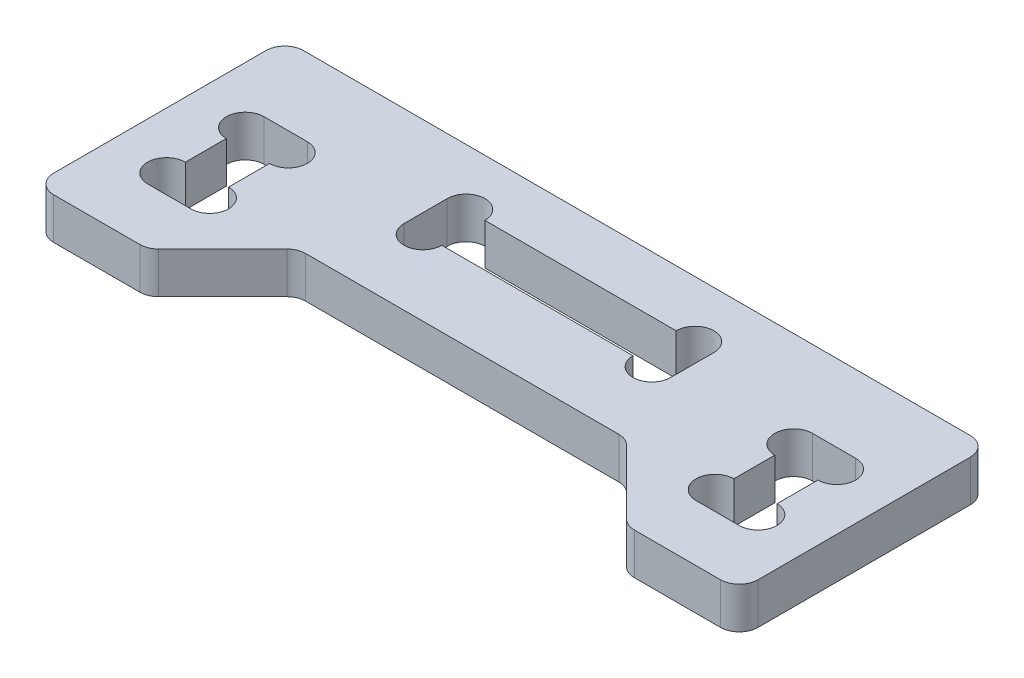
SolidWorks part; units mm, degrees
material "Thornel Mat VMA"
ref_plane "前视基准面" through (0, 0, 0) normal (0, 0, 1) x (1, 0, 0)
ref_plane "上视基准面" through (0, 0, 0) normal (0, 1, 0) x (1, 0, 0)
ref_plane "右视基准面" through (0, 0, 0) normal (1, 0, 0) x (0, 0, -1)
sketch "草图1" plane through (0, 0, 0) normal (0, 1, 0) x (1, 0, 0)
  line L0 (0, 0) -> (0, -4.8464) construction
  line L1 (7.1, -1.15) -> (-7.1, -1.15)
  line L2 (7.1, -1.15) -> (7.1, 1.15)
  line L3 (7.1, 1.15) -> (-7.1, 1.15)
  line L4 (-7.1, -1.15) -> (-7.1, 1.15)
  line L5 (7.1, -1.15) -> (-7.1, 1.15) construction
  line L6 (7.1, 1.15) -> (-7.1, -1.15) construction
  line L7 (-15.75, -6.15) -> (-13.45, -6.15)
  line L8 (-15.75, -6.15) -> (-15.75, 0.05)
  line L9 (-15.75, 0.05) -> (-13.45, 0.05)
  line L10 (-13.45, -6.15) -> (-13.45, 0.05)
  line L11 (-15.75, -6.15) -> (-13.45, 0.05) construction
  line L12 (-15.75, 0.05) -> (-13.45, -6.15) construction
  line L13 (15.75, 0.05) -> (13.45, 0.05)
  line L14 (13.45, -6.15) -> (13.45, 0.05)
  line L15 (15.75, -6.15) -> (13.45, -6.15)
  line L16 (15.75, -6.15) -> (15.75, 0.05)
  line L17 (14.6, 0.05) -> (14.6, -8.6886) construction
  line L18 (-18.75, 4.15) -> (18.75, 4.15)
  line L19 (18.75, 4.15) -> (18.75, -9.15)
  line L20 (18.75, -9.15) -> (12.75, -9.15)
  line L21 (12.75, -9.15) -> (8.75, -5.15)
  line L22 (-8.75, -5.15) -> (8.75, -5.15)
  line L23 (-18.75, 4.15) -> (-18.75, -9.15)
  line L24 (-18.75, -9.15) -> (-12.75, -9.15)
  line L25 (-12.75, -9.15) -> (-8.75, -5.15)
  circle A0 centre (-15.75, -0.955) radius 1.005
  circle A1 centre (-13.45, -0.955) radius 1.005
  circle A2 centre (-13.45, -5.145) radius 1.005
  circle A3 centre (-15.75, -5.145) radius 1.005
  circle A4 centre (13.45, -5.145) radius 1.005
  circle A5 centre (15.75, -5.145) radius 1.005
  circle A6 centre (15.75, -0.955) radius 1.005
  circle A7 centre (13.45, -0.955) radius 1.005
  circle A8 centre (-6.095, 1.15) radius 1.005
  circle A9 centre (-6.095, -1.15) radius 1.005
  circle A10 centre (6.095, -1.15) radius 1.005
  circle A11 centre (6.095, 1.15) radius 1.005
  point P0 (0, 0)
  point P6 (-14.6, -3.05)
  point P43 (-14.6, -6.15)
  dimension "D6" = 2.01
  dimension "D1" = 29.2
  dimension "D2" = 14.2
  dimension "D3" = 2.3
  dimension "D4" = 3.05
  dimension "D5" = 6.2
  dimension "D7" = 3
  dimension "D8" = 3
  dimension "D9" = 3
  dimension "D10" = 4
  dimension "D11" = 45
  dimension "D12" = 6
extrude "凸台-拉伸1" add sketch "草图1" along normal blind 2.2 contours L24 L25 L22 L21 L20 L19 L18 L23 A3 L8 A0 L9 A1 L10 A2 L7 L14 A7 L13 A6 L16 A5 L15 A4 L3 A11 L2 A10 L1 A9 L4 A8
fillet "圆角1" radius 1 8 edges at (-18.75, 1.1, 9.15) (18.75, 1.1, -4.15) (18.75, 1.1, 9.15) (12.75, 1.1, 9.15) (8.75, 1.1, 5.15) (-8.75, 1.1, 5.15) (-12.75, 1.1, 9.15) (-18.75, 1.1, -4.15)
